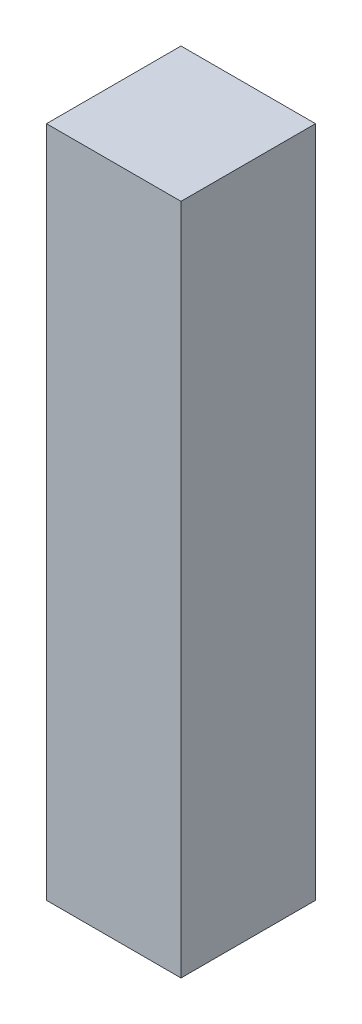
SolidWorks part; units mm, degrees
ref_plane "Plan de face" through (0, 0, 0) normal (0, 0, 1) x (1, 0, 0)
ref_plane "Plan de dessus" through (0, 0, 0) normal (0, 1, 0) x (1, 0, 0)
ref_plane "Plan de droite" through (0, 0, 0) normal (1, 0, 0) x (0, 0, -1)
sketch "Esquisse1" plane through (0, 0, 0) normal (0, 1, 0) x (1, 0, 0)
  line L1 (-15, 15) -> (15, 15)
  line L2 (-15, 15) -> (-15, -15)
  line L3 (-15, -15) -> (15, -15)
  line L4 (15, 15) -> (15, -15)
  point P4 (0, 15)
  point P6 (-15, 0)
  dimension "D1" = 30
  dimension "D2" = 30
extrude "Boss.-Extru.1" add sketch "Esquisse1" along normal blind 150
